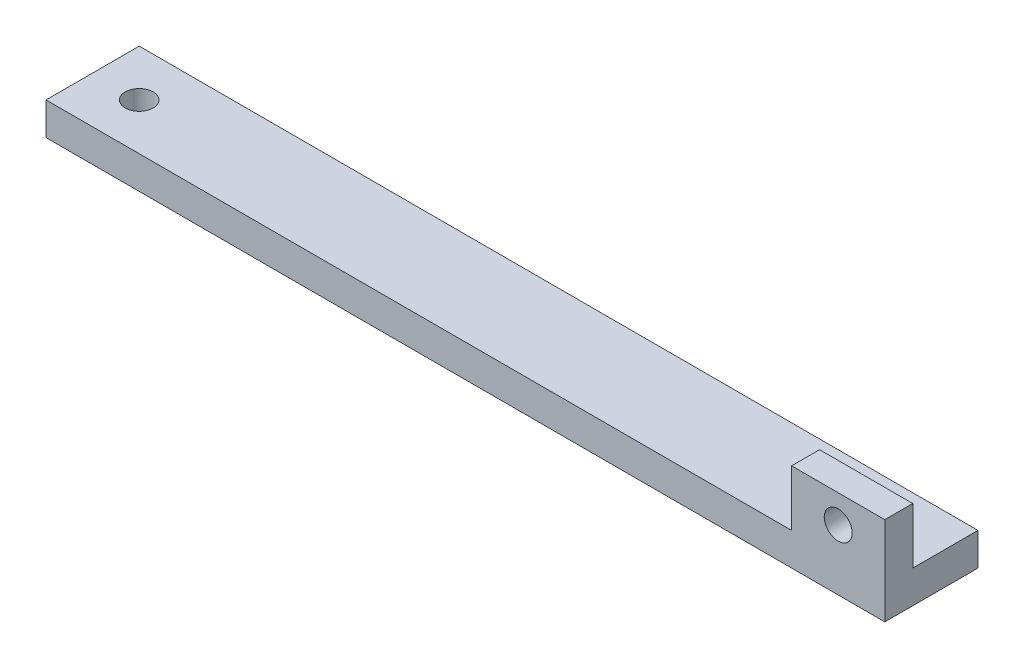
SolidWorks part; units mm, degrees
ref_plane "Front Plane" through (0, 0, 0) normal (0, 0, 1) x (1, 0, 0)
ref_plane "Top Plane" through (0, 0, 0) normal (0, 1, 0) x (1, 0, 0)
ref_plane "Right Plane" through (0, 0, 0) normal (1, 0, 0) x (0, 0, -1)
sketch "Sketch1" plane through (0, 0, 0) normal (0, 1, 0) x (1, 0, 0)
  line L1 (-45, 5) -> (45, 5)
  line L2 (-45, 5) -> (-45, -5)
  line L3 (-45, -5) -> (45, -5)
  line L4 (45, 5) -> (45, -5)
  line L5 (-45, 5) -> (45, -5) construction
  line L6 (-45, -5) -> (45, 5) construction
  circle A0 centre (-40, 0) radius 1.5
  point P0 (0, 0)
  dimension "D3" = 5
  dimension "D1" = 10
  dimension "D2" = 90
extrude "Boss-Extrude1" add sketch "Sketch1" along normal blind 3.5
sketch "Sketch2" plane through (0, 3.5, 0) normal (0, 1, 0) x (1, 0, 0)
  line L1 (45, -5) -> (35, -5)
  line L2 (45, -5) -> (45, -2)
  line L3 (45, -2) -> (35, -2)
  line L4 (35, -5) -> (35, -2)
  dimension "D1" = 3
  dimension "D2" = 10
extrude "Boss-Extrude2" add sketch "Sketch2" along normal blind 6
sketch "Sketch3" plane through (0, 0, 2) normal (0, 0, -1) x (-1, 0, 0)
  line L0 (-45, 9.5) -> (-45, 3.5) construction
  circle A0 centre (-40, 6.5) radius 1.5
  dimension "D1" = 5
extrude "Cut-Extrude1" cut sketch "Sketch3" against normal blind 3
